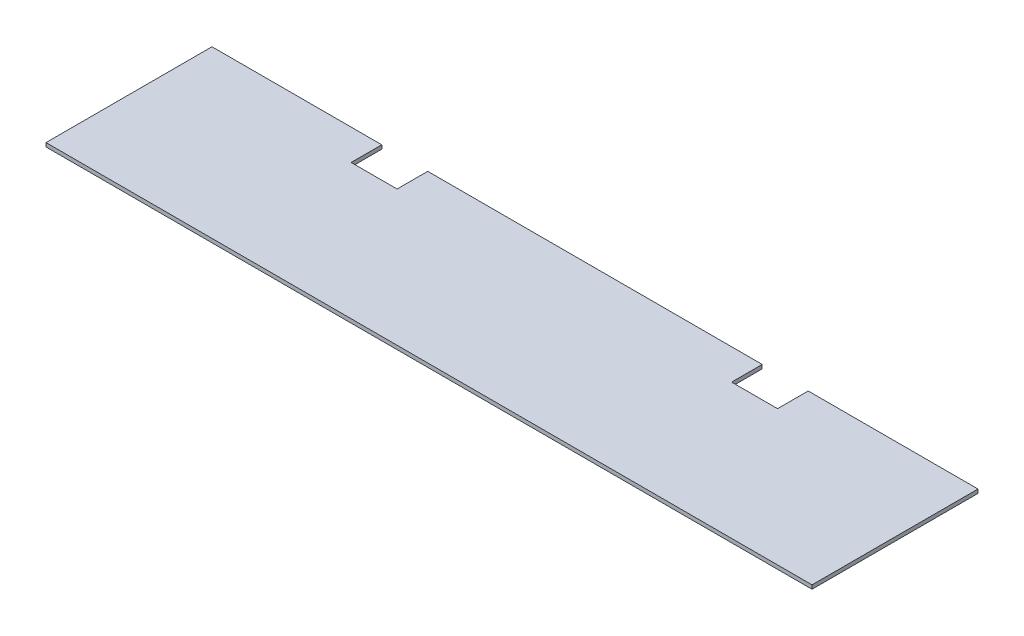
SolidWorks part; units mm, degrees
material "Chapa F.F 1020 - 1,5 mm"
ref_plane "Plano frontal" through (0, 0, 0) normal (0, 0, 1) x (1, 0, 0)
ref_plane "Plano superior" through (0, 0, 0) normal (0, 1, 0) x (1, 0, 0)
ref_plane "Plano direito" through (0, 0, 0) normal (1, 0, 0) x (0, 0, -1)
sketch "Esboço1" plane through (0, 0, 0) normal (0, 1, 0) x (1, 0, 0)
  line L0 (150, 0) -> (150, 94.1187) construction
  line L1 (0, 0) -> (300, 0)
  line L2 (0, 0) -> (0, 65)
  line L3 (0, 65) -> (66.5, 65)
  line L4 (300, 0) -> (300, 65)
  line L5 (66.5, 53) -> (84.5, 53)
  line L6 (66.5, 53) -> (66.5, 65)
  line L7 (233.5, 65) -> (300, 65)
  line L8 (84.5, 53) -> (84.5, 65)
  line L9 (215.5, 53) -> (215.5, 65)
  line L10 (75.5, 53) -> (75.5, 73.0087) construction
  line L11 (233.5, 53) -> (233.5, 65)
  line L12 (233.5, 53) -> (215.5, 53)
  line L13 (84.5, 65) -> (215.5, 65)
  dimension "D1" = 300
  dimension "D2" = 65
  dimension "D3" = 12
  dimension "D4" = 18
  dimension "D5" = 74.5
extrude "Ressalto-extrusão1" add sketch "Esboço1" along normal blind 1.5
